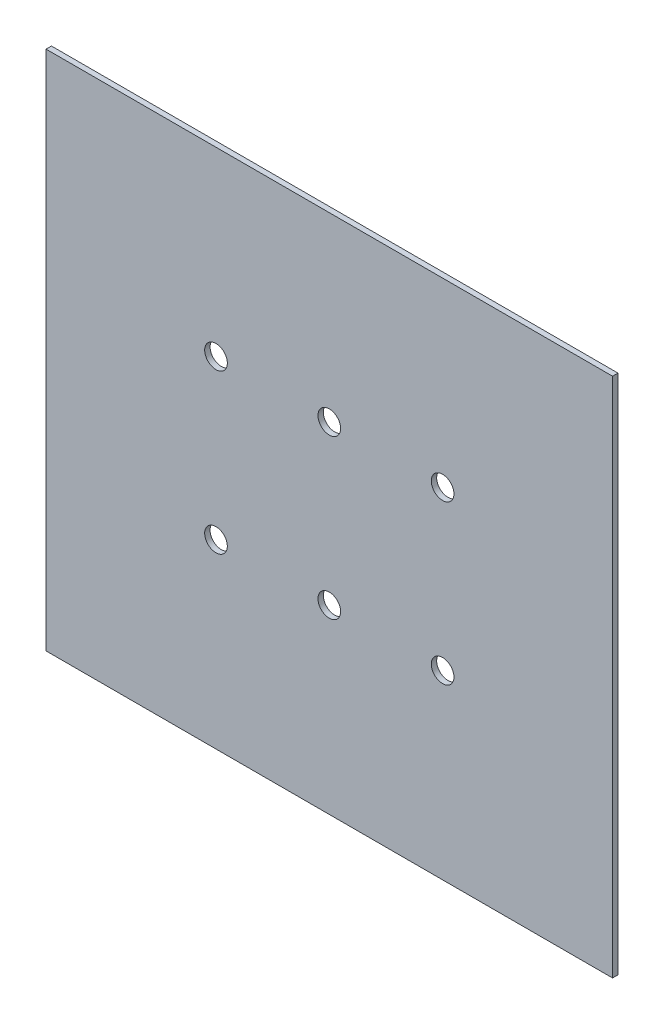
SolidWorks part; units mm, degrees
material "AISI 1020"
ref_plane "Plano frontal" through (0, 0, 0) normal (0, 0, 1) x (1, 0, 0)
ref_plane "Plano superior" through (0, 0, 0) normal (0, 1, 0) x (1, 0, 0)
ref_plane "Plano direito" through (0, 0, 0) normal (1, 0, 0) x (0, 0, -1)
sketch "Esboço1" plane through (0, 0, 0) normal (0, 0, 1) x (1, 0, 0)
  line L0 (-100, 140) -> (-100, 0) construction
  line L1 (0, 0) -> (-200, 0) construction
  line L2 (0, 0) -> (0, 140) construction
  line L3 (0, 140) -> (-200, 140) construction
  line L4 (-200, 0) -> (-200, 140) construction
  line L6 (-230, 180) -> (30, 180) construction
  line L7 (-230, 180) -> (-230, -40) construction
  line L8 (-230, -40) -> (30, -40) construction
  line L9 (30, 180) -> (30, -40) construction
  line L10 (-230, 180) -> (30, -40) construction
  line L11 (-230, -40) -> (30, 180) construction
  line L12 (-350, 300) -> (150, 300)
  line L13 (-350, 300) -> (-350, -160)
  line L14 (-350, -160) -> (150, -160)
  line L15 (150, 300) -> (150, -160)
  line L16 (-350, 300) -> (150, -160) construction
  line L17 (-350, -160) -> (150, 300) construction
  circle A0 centre (0, 0) radius 10
  circle A1 centre (-100, 0) radius 10
  circle A2 centre (-200, 0) radius 10
  circle A3 centre (-200, 140) radius 10
  circle A4 centre (-100, 140) radius 10
  circle A5 centre (0, 140) radius 10
  point P13 (-100, 70)
  point P18 (-100, 70)
  dimension "D3" = 20
  dimension "D1" = 140
  dimension "D2" = 200
  dimension "D4" = 260
  dimension "D5" = 220
  dimension "D6" = 500
  dimension "D7" = 460
extrude "Ressalto-extrusão1" add sketch "Esboço1" along normal blind 4.7625
